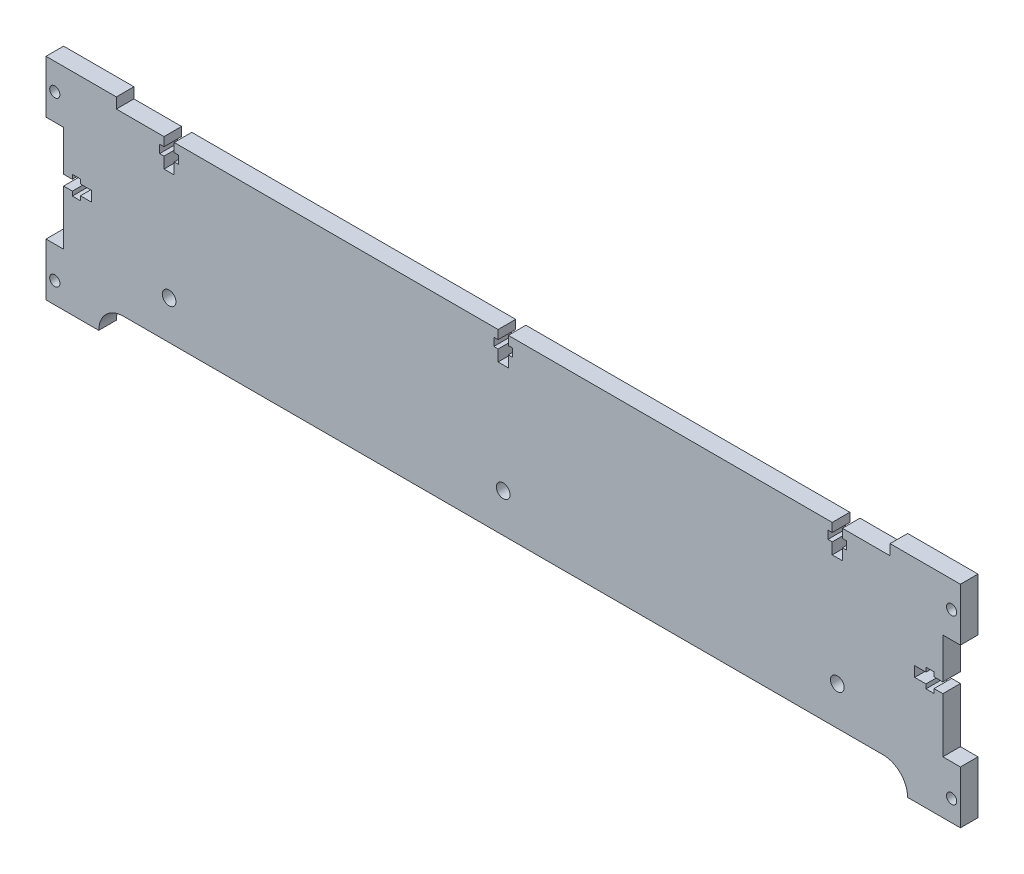
SolidWorks part; units mm, degrees
ref_plane "Front Plane" through (0, 0, 0) normal (0, 0, 1) x (1, 0, 0)
ref_plane "Top Plane" through (0, 0, 0) normal (0, 1, 0) x (1, 0, 0)
ref_plane "Right Plane" through (0, 0, 0) normal (1, 0, 0) x (0, 0, -1)
sketch "Sketch1" plane through (0, 0, 0) normal (0, 0, 1) x (1, 0, 0)
  line L1 (-130, -9) -> (130, -9)
  line L2 (-130, -9) -> (-130, 51)
  line L3 (-130, 51) -> (130, 51)
  line L4 (130, -9) -> (130, 51)
  line L5 (-125, 18) -> (-125, 0) construction
  line L6 (125, 18) -> (125, 0) construction
  line L7 (-110.5, -9) -> (-99.5, -9) construction
  dimension "D1" = 5
  dimension "D2" = 5
  dimension "D3" = 60
extrude "Boss-Extrude1" add sketch "Sketch1" along normal blind 5
sketch "Sketch2" plane through (0, 0, 5) normal (0, 0, 1) x (1, 0, 0)
  line L0 (130, 51) -> (-130, 51) construction
  line L1 (-110, 51) -> (110, 51)
  line L2 (-110, 51) -> (-110, 48)
  line L3 (-110, 48) -> (110, 48)
  line L4 (110, 51) -> (110, 48)
  line L5 (-130, 51) -> (-130, -9) construction
  line L6 (130, -9) -> (130, 51) construction
  line L7 (-125, 36) -> (125, 36) construction
  line L8 (-130, 36) -> (-125, 36)
  line L9 (-130, 36) -> (-130, 6)
  line L10 (-130, 6) -> (-125, 6)
  line L11 (-125, 36) -> (-125, 6)
  line L12 (130, 36) -> (125, 36)
  line L13 (130, 36) -> (130, 6)
  line L14 (130, 6) -> (125, 6)
  line L15 (125, 36) -> (125, 6)
  line L16 (-130, -9) -> (130, -9) construction
  line L17 (-108, -9) -> (108, -9)
  line L18 (-108, -9) -> (-108, -2)
  line L19 (-108, -2) -> (108, -2)
  line L20 (108, -9) -> (108, -2)
  circle A0 centre (-108, -9) radius 7
  circle A1 centre (108, -9) radius 7
  line M9 (-130, 51) -> (-130, -9)
  line M10 (-130, -9) -> (130, -9)
  line M11 (130, -9) -> (130, 51)
  line M12 (130, 51) -> (-130, 51)
  dimension "D8" = 15
  dimension "D9" = 15
  dimension "D1" = 3
  dimension "D2" = 20
  dimension "D3" = 20
  dimension "D4" = 5
  dimension "D5" = 30
  dimension "D6" = 15
  dimension "D7" = 7
extrude "Cut-Extrude1" cut sketch "Sketch2" against normal through all contours L11 L8 L10 M9 | L4 L2 L3 M12 | L12 L15 L14 M11 | A1 L19 A0 L17 | L20 A1 M10 | A1 L20 M10 | L18 A0 M10 | A0 L18 M10
sketch "Sketch3" plane through (0, 0, 5) normal (0, 0, 1) x (1, 0, 0)
  line L4 (-96.45, 40) -> (-93.55, 40)
  line L5 (-96.45, 48) -> (-96.45, 40)
  line L6 (-93.55, 48) -> (-96.45, 48)
  line L7 (-93.55, 40) -> (-93.55, 48)
  line L8 (-96.45, 40) -> (-93.55, 40)
  line L9 (-96.45, 48) -> (-96.45, 40)
  line L10 (-93.55, 48) -> (-96.45, 48)
  line L11 (-93.55, 40) -> (-93.55, 48)
  line L12 (-92.325, 43.2) -> (-92.325, 45.5)
  line L13 (-97.675, 43.2) -> (-92.325, 43.2)
  line L14 (-97.675, 45.5) -> (-97.675, 43.2)
  line L15 (-92.325, 45.5) -> (-97.675, 45.5)
  line L16 (-92.325, 43.2) -> (-92.325, 45.5)
  line L17 (-97.675, 43.2) -> (-92.325, 43.2)
  line L18 (-97.675, 45.5) -> (-97.675, 43.2)
  line L19 (-92.325, 45.5) -> (-97.675, 45.5)
  line L20 (97.675, 45.5) -> (92.325, 45.5)
  line L21 (92.325, 45.5) -> (92.325, 43.2)
  line L22 (92.325, 43.2) -> (97.675, 43.2)
  line L23 (97.675, 43.2) -> (97.675, 45.5)
  line L24 (97.675, 45.5) -> (92.325, 45.5)
  line L25 (92.325, 45.5) -> (92.325, 43.2)
  line L26 (92.325, 43.2) -> (97.675, 43.2)
  line L27 (97.675, 43.2) -> (97.675, 45.5)
  line L28 (93.55, 40) -> (96.45, 40)
  line L29 (93.55, 48) -> (93.55, 40)
  line L30 (96.45, 48) -> (93.55, 48)
  line L31 (96.45, 40) -> (96.45, 48)
  line L32 (93.55, 40) -> (96.45, 40)
  line L33 (93.55, 48) -> (93.55, 40)
  line L34 (96.45, 48) -> (93.55, 48)
  line L35 (96.45, 40) -> (96.45, 48)
  line L36 (125, 24.45) -> (117, 24.45)
  line L37 (117, 24.45) -> (117, 21.55)
  line L38 (117, 21.55) -> (125, 21.55)
  line L39 (125, 21.55) -> (125, 24.45)
  line L40 (125, 24.45) -> (117, 24.45)
  line L41 (117, 24.45) -> (117, 21.55)
  line L42 (117, 21.55) -> (125, 21.55)
  line L43 (125, 21.55) -> (125, 24.45)
  line L44 (-2.675, 43.2) -> (2.675, 43.2)
  line L45 (-2.675, 45.5) -> (-2.675, 43.2)
  line L46 (2.675, 45.5) -> (-2.675, 45.5)
  line L47 (2.675, 43.2) -> (2.675, 45.5)
  line L48 (-2.675, 43.2) -> (2.675, 43.2)
  line L49 (-2.675, 45.5) -> (-2.675, 43.2)
  line L50 (2.675, 45.5) -> (-2.675, 45.5)
  line L51 (2.675, 43.2) -> (2.675, 45.5)
  line L52 (1.45, 48) -> (-1.45, 48)
  line L53 (1.45, 40) -> (1.45, 48)
  line L54 (-1.45, 40) -> (1.45, 40)
  line L55 (-1.45, 48) -> (-1.45, 40)
  line L56 (1.45, 48) -> (-1.45, 48)
  line L57 (1.45, 40) -> (1.45, 48)
  line L58 (-1.45, 40) -> (1.45, 40)
  line L59 (-1.45, 48) -> (-1.45, 40)
  line L60 (-117, 21.55) -> (-117, 24.45)
  line L61 (-125, 21.55) -> (-117, 21.55)
  line L62 (-125, 24.45) -> (-125, 21.55)
  line L63 (-117, 24.45) -> (-125, 24.45)
  line L64 (-117, 21.55) -> (-117, 24.45)
  line L65 (-125, 21.55) -> (-117, 21.55)
  line L66 (-125, 24.45) -> (-125, 21.55)
  line L67 (-117, 24.45) -> (-125, 24.45)
  line L68 (-120.2, 20.325) -> (-120.2, 25.675)
  line L69 (-120.2, 25.675) -> (-122.5, 25.675)
  line L70 (-122.5, 25.675) -> (-122.5, 20.325)
  line L71 (-122.5, 20.325) -> (-120.2, 20.325)
  line L72 (-120.2, 20.325) -> (-120.2, 25.675)
  line L73 (-120.2, 25.675) -> (-122.5, 25.675)
  line L74 (-122.5, 25.675) -> (-122.5, 20.325)
  line L75 (-122.5, 20.325) -> (-120.2, 20.325)
  line L76 (120.2, 20.325) -> (122.5, 20.325)
  line L77 (120.2, 25.675) -> (120.2, 20.325)
  line L78 (122.5, 25.675) -> (120.2, 25.675)
  line L79 (122.5, 20.325) -> (122.5, 25.675)
  line L80 (120.2, 20.325) -> (122.5, 20.325)
  line L81 (120.2, 25.675) -> (120.2, 20.325)
  line L82 (122.5, 25.675) -> (120.2, 25.675)
  line L83 (122.5, 20.325) -> (122.5, 25.675)
  circle A1 centre (-127.5, 43.5) radius 1.45
  circle A2 centre (-127.5, 43.5) radius 1.45
  circle A3 centre (-127.5, -3) radius 1.45
  circle A4 centre (-127.5, -3) radius 1.45
  circle A5 centre (127.5, -3) radius 1.45
  circle A6 centre (127.5, -3) radius 1.45
  circle A7 centre (127.5, 43.5) radius 1.45
  circle A8 centre (127.5, 43.5) radius 1.45
  circle A9 centre (-95, 9) radius 1.95
  circle A10 centre (-95, 9) radius 1.95
  circle A11 centre (95, 9) radius 1.95
  circle A12 centre (95, 9) radius 1.95
  circle A13 centre (0, 9) radius 1.95
  circle A14 centre (0, 9) radius 1.95
  point P52 (0, 0)
  point P53 (0, 0)
  point P63 (0, 0)
  point P64 (0, 0)
  point P65 (0, 0)
  line M45 (-125, 36) -> (-125, 6)
  dimension "D1" = 0
  dimension "D2" = 0
  dimension "D3" = 0
  dimension "D4" = 0
  dimension "D5" = 0
  dimension "D6" = 0
  dimension "D7" = 0
  dimension "D8" = 0
  dimension "D9" = 0
  dimension "D10" = 0
  dimension "D11" = 0
  dimension "D12" = 0
  dimension "D13" = 0
  dimension "D14" = 0
  dimension "D15" = 0
  dimension "D16" = 0
  dimension "D17" = 0
extrude "Cut-Extrude2" cut sketch "Sketch3" against normal through all and the other way through all contours A2 | L72 L65 L64 L67 | L67 L74 L65 L72 | L74 L67 L65 M45 | L74 L75 L72 L65 | A10 | A4 | L8 L11 L10 L9 | L18 L17 L16 L19 | L58 L57 L56 L59 | L49 L48 L51 L50 | A14 | L32 L35 L34 L33 | L25 L26 L27 L24 | A12 | L42 L43 L40 L41 | L80 L83 L82 L81 | A6 | A8
